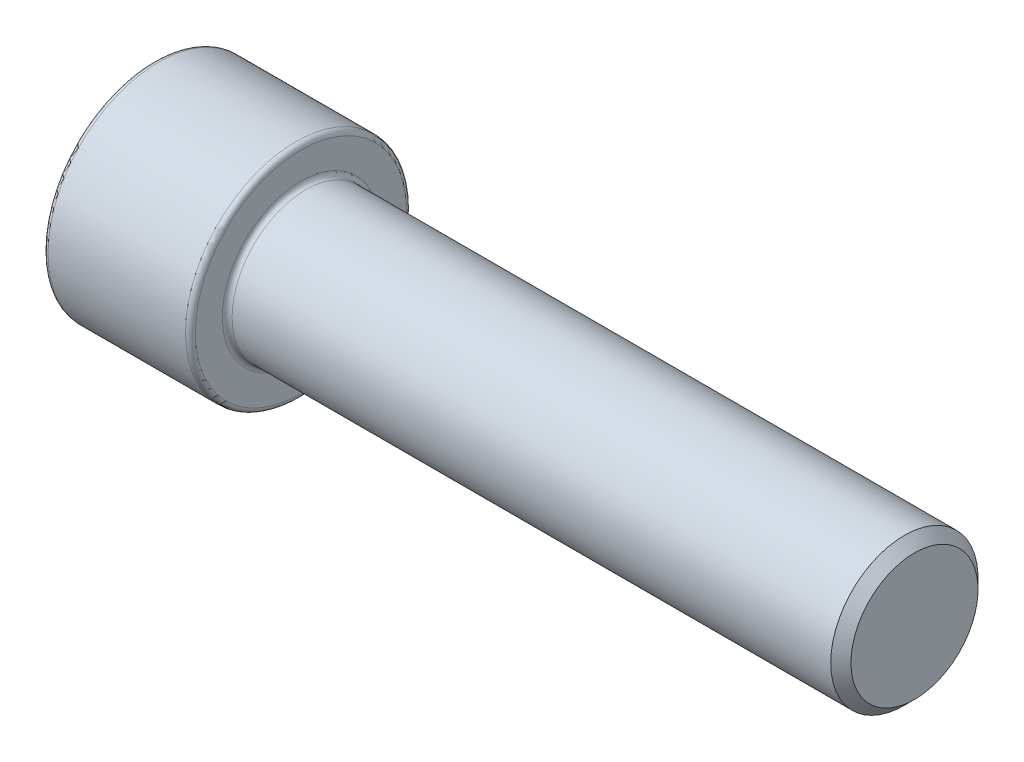
SolidWorks part; units mm, degrees
material "Alloy Steel"
ref_plane "Front Plane" through (0, 0, 0) normal (0, 0, 1) x (1, 0, 0)
ref_plane "Top Plane" through (0, 0, 0) normal (0, 1, 0) x (1, 0, 0)
ref_plane "Right Plane" through (0, 0, 0) normal (1, 0, 0) x (0, 0, -1)
sketch "BaseHeadSke" plane through (0, 0, 0) normal (1, 0, 0) x (0, 0, -1)
  circle A1 centre (0, 0) radius 18
  dimension "Head_diameter" = 36
extrude "BaseHead" add sketch "BaseHeadSke" along normal blind 24
sketch "BodySke" plane through (0, 0, 0) normal (0, 0, 1) x (1, 0, 0)
  line L0 (0, 0) -> (124, 0)
  line L1 (124, 0) -> (124, 10.352)
  line L2 (124, 10.352) -> (122.352, 12)
  line L3 (122.352, 12) -> (0, 12)
  line L4 (0, 12) -> (0, 0)
  line L6 (0, 0) -> (159.3976, 0) construction
  line L7 (64, -84.3176) -> (64, 77.7215) construction
  line L8 (121, -21.5941) -> (121, 39.2994) construction
  line L10 (24, -18) -> (24, 18) construction
  dimension "Ang" = 45
  dimension "Diameter" = 24
  dimension "Minor_dia" = 20.704
  dimension "Thread_length" = 60
  dimension "Advance" = 3
  dimension "Length" = 100
revolve "BaseBody" add sketch "BodySke" angle 360 about L6
cosmetic thread "ThreadCosmetic" [suppressed] parameters "Thread_length"=60, "Thread_minor"=20.704
sketch "CutSocketSke" plane through (0, 0, 0) normal (1, 0, 0) x (0, 0, -1)
  line L1 (0, 10.9697) -> (-9.5, 5.4848)
  line L2 (-9.5, 5.4848) -> (-9.5, -5.4848)
  line L3 (-9.5, -5.4848) -> (0, -10.9697)
  line L4 (0, -10.9697) -> (9.5, -5.4848)
  line L5 (9.5, -5.4848) -> (9.5, 5.4848)
  line L6 (9.5, 5.4848) -> (0, 10.9697)
  circle A0 centre (0, 0) radius 9.5 construction
  dimension "Socket_width" = 19
extrude "CutSocket" cut sketch "CutSocketSke" along normal blind 12
sketch "CutHoleSke" plane through (0, 0, 0) normal (0, 0, 1) x (1, 0, 0)
  line L0 (0, 0) -> (149.4323, 0) construction
  line L1 (0, 9.5) -> (13.6, 9.5)
  line L2 (13.6, 9.5) -> (19.0848, 0)
  line L3 (19.0848, 0) -> (0, 0)
  line L4 (0, 0) -> (0, 9.5)
  line L6 (24, -18) -> (24, 18) construction
  dimension "D1" = 60
  dimension "Hole_depth" = 10.4
  dimension "D2" = 19
revolve "CutHole" cut sketch "CutHoleSke" angle 360 about L0
fillet "Fillet" radius 0.8 3 edges at (24, 0, -12) (24, 0, -18) (0, 0, -18)
sketch "ThdSchSke" plane through (0, 0, 0) normal (0, 0, 1) x (1, 0, 0)
  line L0 (120.0485, 13.9029) -> (120.0485, 12)
  line L1 (120.0485, 12) -> (121, 10.352)
  line L2 (121, 10.352) -> (121.9515, 12)
  line L3 (121.9515, 12) -> (121.9515, 13.9029)
  line L4 (121.9515, 13.9029) -> (120.0485, 13.9029)
  line L6 (0, 0) -> (141.9934, 0) construction
  line L7 (124, -10.352) -> (124, 10.352) construction
  dimension "Advance" = 3
  dimension "D2" = 20.704
  dimension "D3" = 24
revolve "ThreadSchematic" [suppressed] cut sketch "ThdSchSke" angle 360 about L6
pattern_linear "ThdSchPat" [suppressed] count 19 spacing 3 along (1, 0, 0)
equation "\"Thread_minor@ThreadCosmetic\" = \"Minor_dia@BodySke\""
equation "\"Thread_length@ThreadCosmetic\" = \"Thread_length@BodySke\""
equation "\"D2@CutHoleSke\" = \"Socket_width@CutSocketSke\""
equation "\"D2@ThdSchSke\" = \"Minor_dia@BodySke\""
equation "\"D3@ThdSchSke\" = \"Diameter@BodySke\""
equation "\"Advance@ThdSchSke\" = \"Advance@BodySke\""
equation "\"D3@ThdSchPat\" = \"Advance@BodySke\""
equation "\"D1@ThdSchPat\" =  int( \"Thread_length@BodySke\"/\"Advance@BodySke\" )-1"
equation "\"Mass\"= \"SW-질량\" / 1000"
